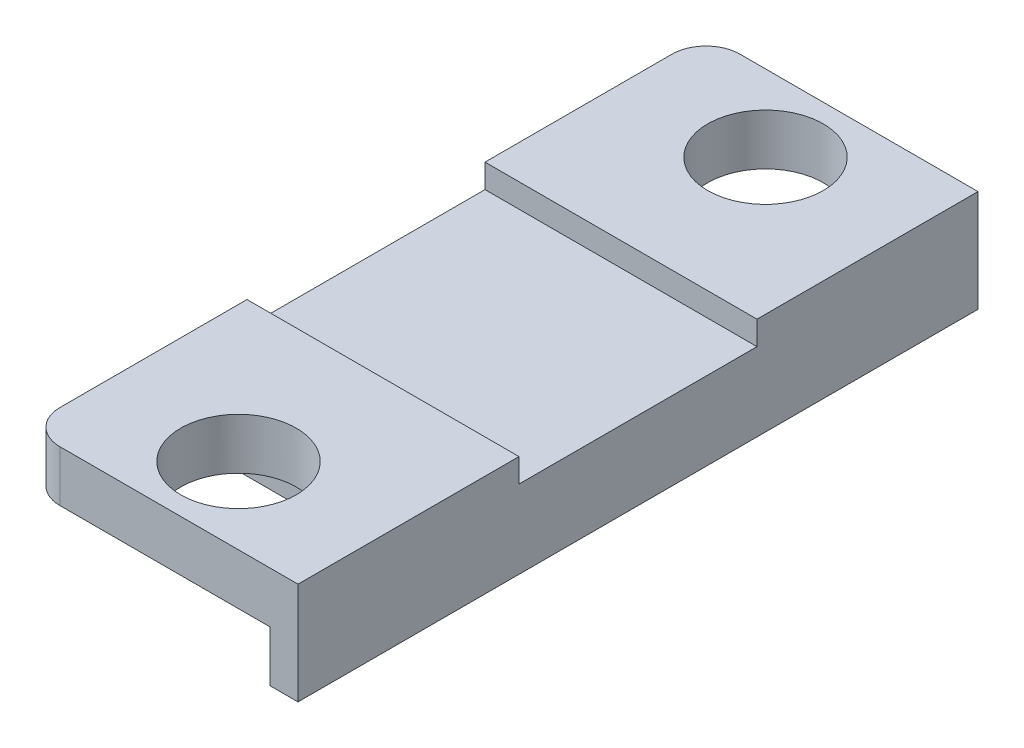
SolidWorks part; units mm, degrees
ref_plane "Alzado" through (0, 0, 0) normal (0, 0, 1) x (1, 0, 0)
ref_plane "Planta" through (0, 0, 0) normal (0, 1, 0) x (1, 0, 0)
ref_plane "Vista lateral" through (0, 0, 0) normal (1, 0, 0) x (0, 0, -1)
sketch "Croquis1" plane through (0, 0, 0) normal (0, 1, 0) x (1, 0, 0)
  line L0 (161.9623, -17) -> (161.9623, -7) construction
  line L1 (161.9623, -2) -> (169.9623, -2)
  line L2 (161.9623, -2) -> (161.9623, -22)
  line L3 (161.9623, -22) -> (169.9623, -22)
  line L4 (169.9623, -2) -> (169.9623, -22)
  line L5 (169.9623, -3) -> (169.9623, -21) construction
  circle A0 centre (165.9623, -4.25) radius 1.7
  circle A1 centre (165.9623, -19.75) radius 1.7
  circle A2 centre (165.9623, -4.25) radius 1.7 construction
  circle A3 centre (165.9623, -19.75) radius 1.7 construction
  dimension "D1" = 20
extrude "Saliente-Extruir1" add sketch "Croquis1" against normal blind 3 separate body
sketch "Croquis2" plane through (0, -3, 0) normal (0, -1, 0) x (1, 0, 0)
  line L0 (161.9623, 2) -> (161.9623, 22) construction
  line L1 (167.55, 22.5) -> (164.3746, 22.5) construction
  line L2 (164.3746, 22.5) -> (162.7869, 19.75) construction
  line L3 (162.7869, 19.75) -> (164.3746, 17) construction
  line L4 (164.3746, 17) -> (167.55, 17)
  line L5 (167.55, 17) -> (169.1377, 19.75)
  line L6 (169.1377, 19.75) -> (167.55, 22.5) construction
  line L7 (161.9623, 12) -> (169.9623, 12) construction
  line L8 (169.9623, 22) -> (169.9623, 2) construction
  line L9 (169.1377, 19.75) -> (169.1377, 22)
  line L10 (161.9623, 22) -> (169.9623, 22) construction
  line L11 (169.1377, 22) -> (161.9623, 22)
  line L12 (161.9623, 22) -> (161.9623, 17)
  line L13 (161.9623, 17) -> (164.3746, 17)
  line L14 (169.1377, 4.25) -> (167.55, 1.5) construction
  line L15 (162.7869, 4.25) -> (164.3746, 7) construction
  line L16 (164.3746, 1.5) -> (162.7869, 4.25) construction
  line L17 (167.55, 1.5) -> (164.3746, 1.5) construction
  line L18 (161.9623, 7) -> (164.3746, 7)
  line L19 (161.9623, 2) -> (161.9623, 7)
  line L20 (169.1377, 2) -> (161.9623, 2)
  line L21 (169.1377, 4.25) -> (169.1377, 2)
  line L22 (167.55, 7) -> (169.1377, 4.25)
  line L23 (164.3746, 7) -> (167.55, 7)
  circle A0 centre (165.9623, 19.75) radius 2.75 construction
  circle A1 centre (165.9623, 4.25) radius 2.75 construction
  dimension "D1" = 5.5
extrude "Cortar-Extruir2" cut sketch "Croquis2" against normal blind 1.5
sketch "Croquis3" plane through (161.9623, 0, 0) normal (-1, 0, 0) x (0, 0, 1)
  line L0 (12, -3) -> (12, 0) construction
  line L1 (7, -3) -> (17, -3) construction
  line L2 (2, 0) -> (22, 0) construction
  line L4 (8.5, -1) -> (15.5, -1)
  line L5 (8.5, -1) -> (8.5, 0)
  line L6 (8.5, 0) -> (15.5, 0)
  line L7 (15.5, -1) -> (15.5, 0)
  line L8 (8.5, -1) -> (15.5, 0) construction
  line L9 (8.5, 0) -> (15.5, -1) construction
  point P6 (12, -0.5)
  dimension "D1" = 7
  dimension "D2" = 1
extrude "Cortar-Extruir3" cut sketch "Croquis3" against normal up to next
fillet "Redondeo1" radius 1 3 edges at (161.9623, -0.75, 2) (161.9623, -0.75, 22) (161.9623, -3, 12)
sketch "Croquis4" plane through (0, -1, 0) normal (0, 1, 0) x (1, 0, 0)
  line L1 (169.9623, -8.5) -> (161.9623, -8.5)
  line L2 (169.9623, -8.5) -> (169.9623, -15.5)
  line L3 (169.9623, -15.5) -> (161.9623, -15.5)
  line L4 (161.9623, -8.5) -> (161.9623, -15.5)
extrude "Saliente-Extruir2" add sketch "Croquis4" along normal blind 0.3
